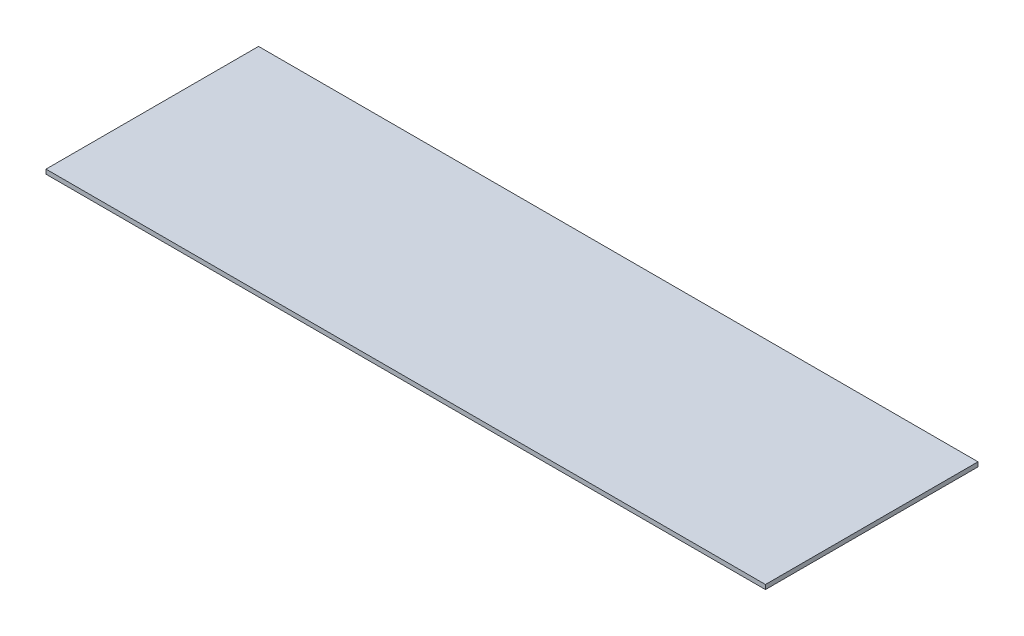
SolidWorks part; units mm, degrees
material "Pine"
ref_plane "Front Plane" through (0, 0, 0) normal (0, 0, 1) x (1, 0, 0)
ref_plane "Top Plane" through (0, 0, 0) normal (0, 1, 0) x (1, 0, 0)
ref_plane "Right Plane" through (0, 0, 0) normal (1, 0, 0) x (0, 0, -1)
sketch "Sketch1" plane through (0, 0, 0) normal (0, 1, 0) x (1, 0, 0)
  line L1 (-515.874, 152.4) -> (515.874, 152.4)
  line L2 (-515.874, 152.4) -> (-515.874, -152.4)
  line L3 (-515.874, -152.4) -> (515.874, -152.4)
  line L4 (515.874, 152.4) -> (515.874, -152.4)
  line L5 (-515.874, 152.4) -> (515.874, -152.4) construction
  line L6 (-515.874, -152.4) -> (515.874, 152.4) construction
  point P0 (0, 0)
  dimension "D1" = 1031.748
extrude "Boss-Extrude1" add sketch "Sketch1" along normal blind 6.35
